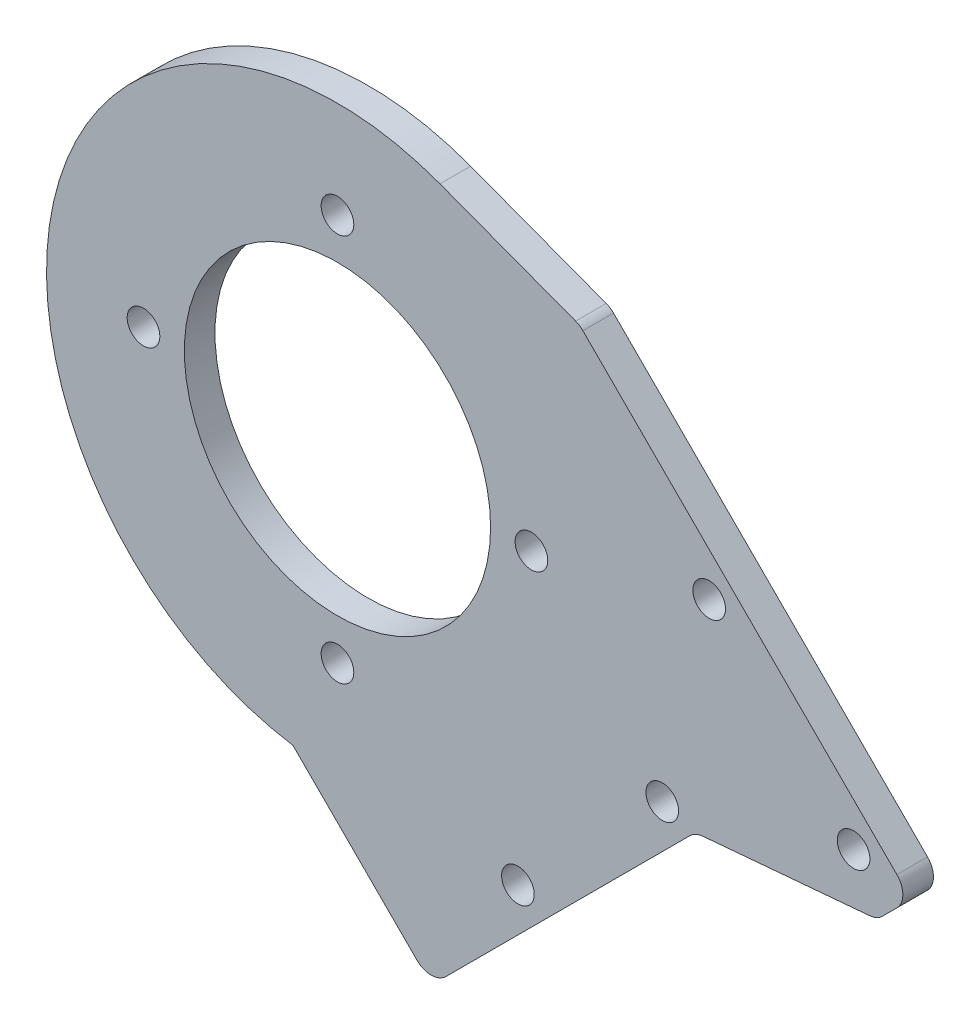
SolidWorks part; units mm, degrees
material "Thornel Mat VMA"
ref_plane "前视基准面" through (0, 0, 0) normal (0, 0, 1) x (1, 0, 0)
ref_plane "上视基准面" through (0, 0, 0) normal (0, 1, 0) x (1, 0, 0)
ref_plane "右视基准面" through (0, 0, 0) normal (1, 0, 0) x (0, 0, -1)
sketch "草图1" plane through (0, 0, 0) normal (0, 0, 1) x (1, 0, 0)
  circle A0 centre (0, 0) radius 19 construction
  circle A1 centre (0, 19) radius 1.6
  circle A2 centre (0, 0) radius 28.5
  circle A3 centre (0, 0) radius 15
  circle A4 centre (19, 0) radius 1.6
  circle A5 centre (0, -19) radius 1.6
  circle A6 centre (-19, 0) radius 1.6
  point P16 (0, 0)
  dimension "D1" = 38
  dimension "D2" = 3.2
  dimension "D4" = 30
  dimension "D5" = 57
  dimension "D3" = 4
extrude "凸台-拉伸1" add sketch "草图1" along normal blind 3
sketch "草图2" plane through (0, 0, 3) normal (0, 0, 1) x (1, 0, 0)
  line L0 (24.0416, 21.2132) -> (54.8008, -9.5459)
  line L1 (22.6274, 22.6274) -> (0, 0) construction
  line L3 (0, 0) -> (69.4053, 0) construction
  line L5 (7.7782, -40.3051) -> (-4.3628, -28.1641)
  line L6 (36.416, 4.5962) -> (50.5581, -9.5459) construction
  line L7 (10.6066, -40.3051) -> (34.5344, -16.3773)
  line L8 (35.7743, -15.7992) -> (52.1467, -14.3668)
  line L9 (54.8008, -12.3744) -> (53.3866, -13.7886)
  line L10 (21.2132, 21.2132) -> (20.1525, 20.1525)
  line L11 (31.8198, -14.8492) -> (17.6777, -28.9914) construction
  circle A0 centre (0, 0) radius 28.5 construction
  arc A1 (-4.3628, -28.1641) -> (28.5, 0) centre (0, 0) ccw
  circle A3 centre (50.5581, -9.5459) radius 1.6
  circle A5 centre (36.416, 4.5962) radius 1.6
  arc A6 (10.6066, -40.3051) -> (7.7782, -40.3051) centre (9.1924, -38.8909) cw
  arc A7 (34.5344, -16.3773) -> (35.7743, -15.7992) centre (35.9486, -17.7915) cw
  arc A8 (54.8008, -9.5459) -> (54.8008, -12.3744) centre (53.3866, -10.9602) cw
  arc A9 (52.1467, -14.3668) -> (53.3866, -13.7886) centre (51.9723, -12.3744) ccw
  arc A10 (-4.3628, -28.1641) -> (20.1525, 20.1525) centre (0, 0) ccw
  arc A11 (24.0416, 21.2132) -> (21.2132, 21.2132) centre (22.6274, 19.799) ccw
  circle A12 centre (17.6777, -28.9914) radius 1.6
  circle A13 centre (31.8198, -14.8492) radius 1.6
  circle M16 centre (0, 0) radius 28.5
  dimension "D2" = 3.2
  dimension "D3" = 3
  dimension "D4" = 2
  dimension "D8" = 55
  dimension "D9" = 2
  dimension "D11" = 2
  dimension "D13" = 2
  dimension "D19" = 3.2
  dimension "D1" = 45
  dimension "D5" = 36
  dimension "D6" = 20
  dimension "D7" = 42.5
  dimension "D10" = 5
  dimension "D12" = 32
  dimension "D14" = 2
  dimension "D15" = 140
  dimension "D16" = 15
  dimension "D17" = 20
  dimension "D18" = 3
extrude "凸台-拉伸2" add sketch "草图2" against normal up to surface (3 mm away) contours L8 A9 L9 A8 L0 L10 L5 A6 L7 A7 A3 A5 M16 up to face at (28.5, 0, 0)
sketch "草图4" plane through (0, 0, 3) normal (0, 0, 1) x (1, 0, 0)
  line L0 (10.0382, 26.6737) -> (23.3319, 21.6708)
  line L1 (21.2132, 21.2132) -> (20.1525, 20.1525) construction
  line L2 (21.2132, 21.2132) -> (20.1525, 20.1525)
  arc A0 (20.1525, 20.1525) -> (-4.3628, -28.1641) centre (0, 0) ccw construction
  arc A1 (24.0416, 21.2132) -> (21.2132, 21.2132) centre (22.6274, 19.799) ccw construction
  arc A3 (23.3319, 21.6708) -> (21.2132, 21.2132) centre (22.6274, 19.799) ccw
  arc A5 (20.1525, 20.1525) -> (10.0382, 26.6737) centre (0, 0) ccw
extrude "凸台-拉伸3" add sketch "草图4" against normal up to surface (3 mm away) up to face at (27.679, -9.2955, 0)
